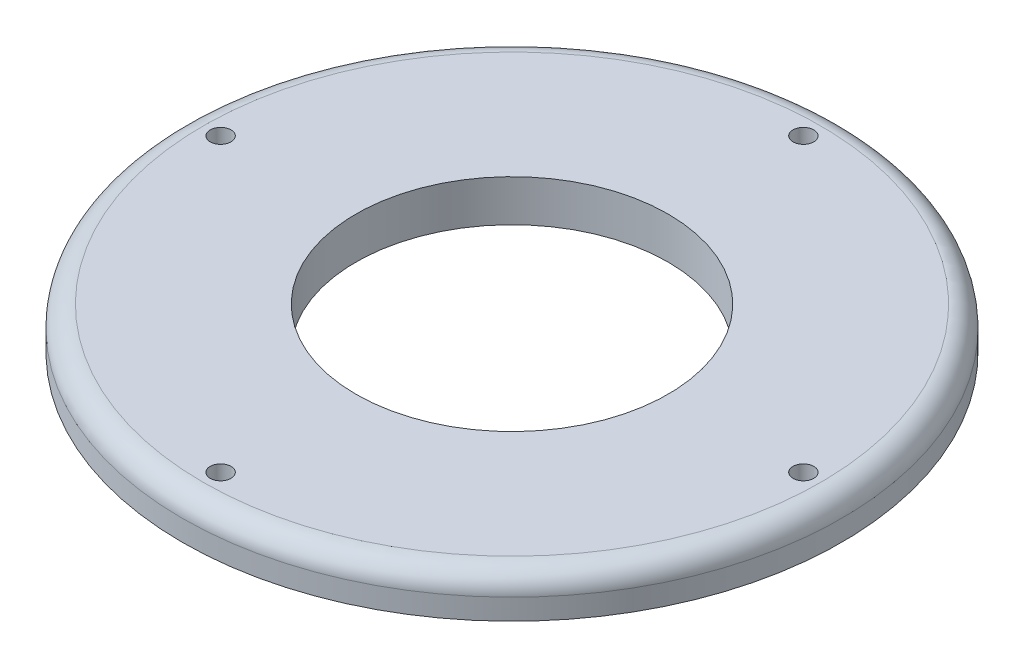
SolidWorks part; units mm, degrees
ref_plane "Front Plane" through (0, 0, 0) normal (0, 0, 1) x (1, 0, 0)
ref_plane "Top Plane" through (0, 0, 0) normal (0, 1, 0) x (1, 0, 0)
ref_plane "Right Plane" through (0, 0, 0) normal (1, 0, 0) x (0, 0, -1)
sketch "Sketch1" plane through (0, 0, 0) normal (0, 1, 0) x (1, 0, 0)
  circle A0 centre (0, 0) radius 47.5
  dimension "D1" = 95
extrude "Boss-Extrude1" add sketch "Sketch1" along normal blind 6
sketch "Sketch2" plane through (0, 6, 0) normal (0, 1, 0) x (1, 0, 0)
  circle A0 centre (0, 42) radius 1.5
  circle A1 centre (42, 0) radius 1.5
  circle A2 centre (0, -42) radius 1.5
  circle A3 centre (-42, 0) radius 1.5
  point P12 (0, 0)
  dimension "D1" = 42
  dimension "D3" = 3
  dimension "D2" = 4
extrude "Cut-Extrude1" cut sketch "Sketch2" against normal through all
sketch "Sketch3" plane through (0, 6, 0) normal (0, 1, 0) x (1, 0, 0)
  circle A0 centre (0, 0) radius 22.5
extrude "Cut-Extrude2" cut sketch "Sketch3" against normal through all
fillet "Fillet1" radius 3 1 edges at (0, 6, 47.5)
